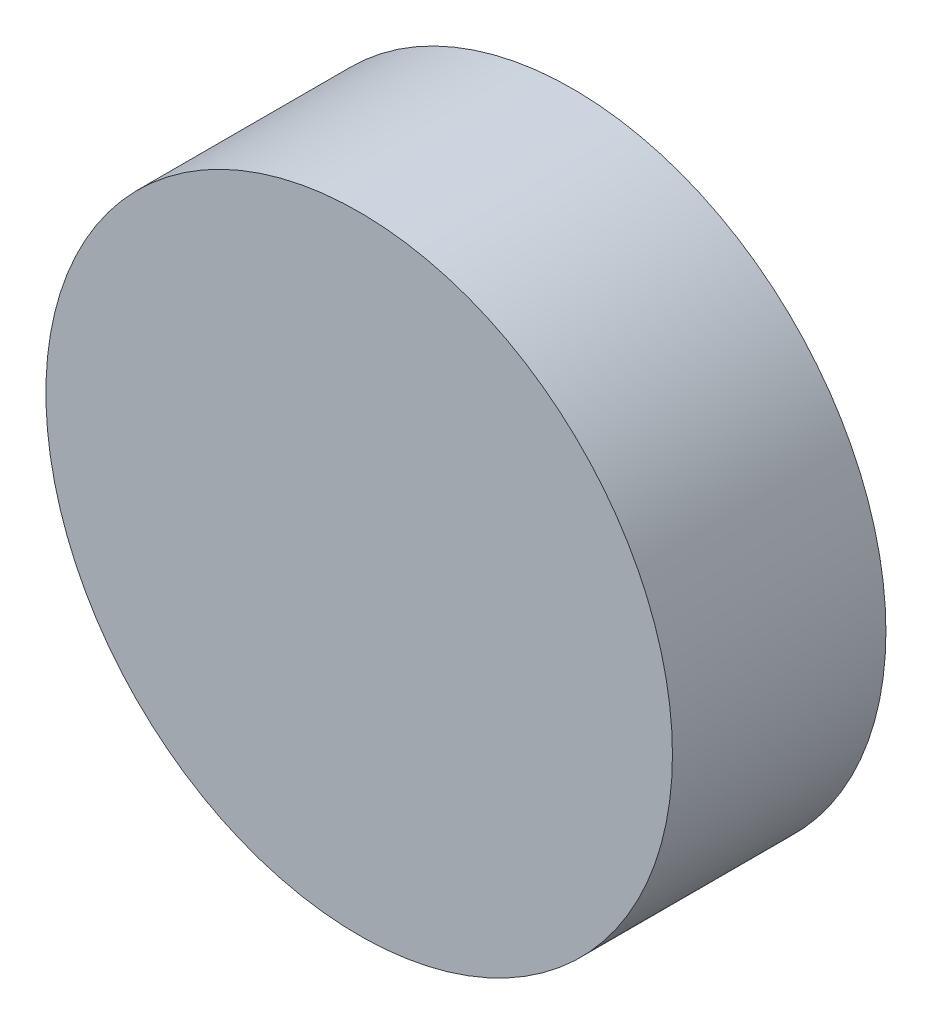
SolidWorks part; units mm, degrees
ref_plane "前视基准面" through (0, 0, 0) normal (0, 0, 1) x (1, 0, 0)
ref_plane "上视基准面" through (0, 0, 0) normal (0, 1, 0) x (1, 0, 0)
ref_plane "右视基准面" through (0, 0, 0) normal (1, 0, 0) x (0, 0, -1)
other "Configuration Table"
sketch "草图3" plane through (0, 0, 0) normal (0, 0, 1) x (1, 0, 0)
  circle A0 centre (0, 0) radius 29.3507
extrude "凸台-拉伸1" add sketch "草图3" along normal blind 20 contours A0
sketch "草图6" plane through (0, 0, 20) normal (0, 0, 1) x (1, 0, 0)
  circle A0 centre (0, 0) radius 29.3507 construction
  circle A1 centre (0, 0) radius 29.3507
  circle A2 centre (0, 0) radius 29.3507 construction
  circle A3 centre (0, 0) radius 29.3507
  circle A4 centre (0, 0) radius 29.3507
  circle A5 centre (0, 0) radius 29.3507
  circle A6 centre (0, 0) radius 29.3507
  circle A7 centre (0, 0) radius 29.3507
  dimension "D1" = 0
  dimension "D2" = 0
sketch "草图9" plane through (0, 0, 20) normal (0, 0, 1) x (1, 0, 0)
  line L0 (-94.9712, 20.3693) -> (-85.033, -14.8465)
  line L1 (-106.5201, 17.1101) -> (-96.5819, -18.1057)
  line L2 (-129.6974, 32.31) -> (-126.6442, 26.3112)
  line L3 (-126.6442, 26.3112) -> (-122.204, -23.084)
  line L4 (129.7937, -26.2075) -> (92.7843, -58.3889)
  line L5 (-210.1493, 68.9881) -> (-162.5485, 9.1286)
  circle A2 centre (0, 0) radius 39.3507
  circle A3 centre (0, 0) radius 39.3507
  circle A4 centre (0, 0) radius 22.3507
  circle A5 centre (0, 0) radius 5.3507
  dimension "D1" = 10
  dimension "D2" = 17
  dimension "D3" = 17
  dimension "D4" = 12
